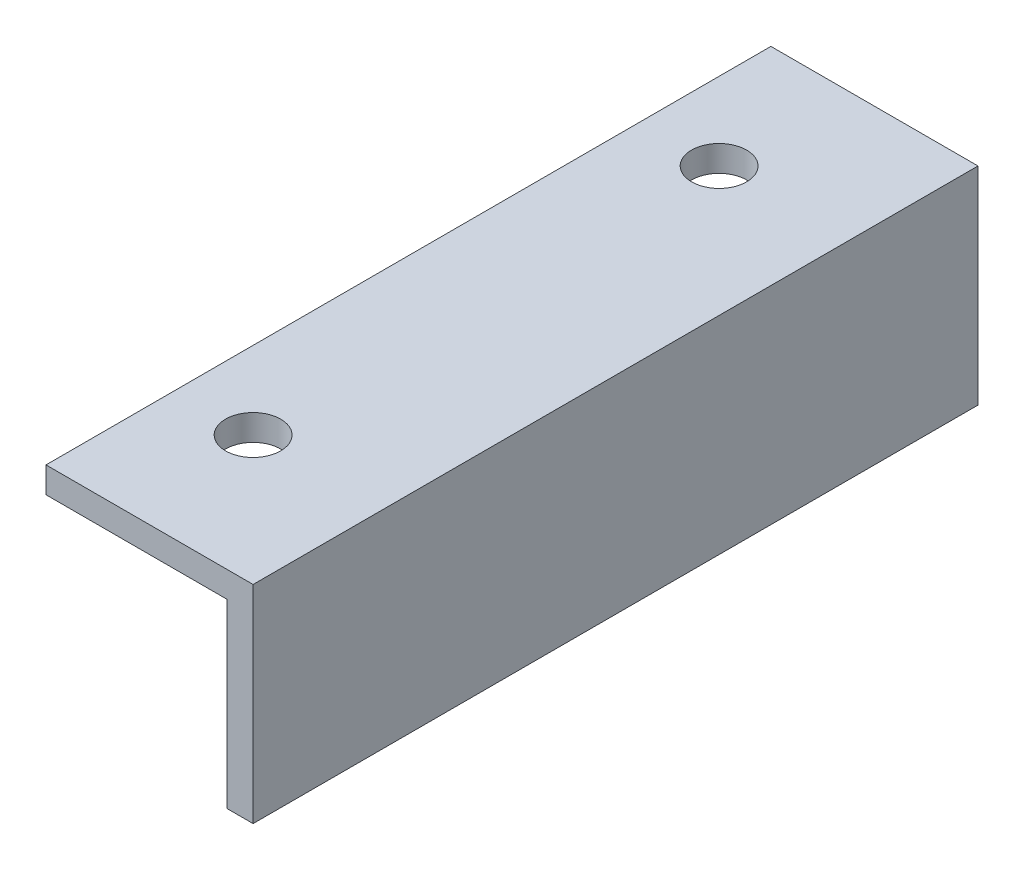
SolidWorks part; units mm, degrees
material "6061 Alloy"
ref_plane "Front" through (0, 0, 0) normal (0, 0, 1) x (1, 0, 0)
ref_plane "Top" through (0, 0, 0) normal (0, 1, 0) x (1, 0, 0)
ref_plane "Right" through (0, 0, 0) normal (1, 0, 0) x (0, 0, -1)
sketch "Sketch1" plane through (0, 0, 0) normal (0, 0, 1) x (1, 0, 0)
  line L0 (0, 0) -> (0, 25.4)
  line L1 (0, 25.4) -> (-25.4, 25.4)
  line L2 (-25.4, 25.4) -> (-25.4, 22.225)
  line L3 (-25.4, 22.225) -> (-3.175, 22.225)
  line L4 (-3.175, 22.225) -> (-3.175, 0)
  line L5 (-3.175, 0) -> (0, 0)
  dimension "D1" = 25.4
  dimension "D2" = 3.175
extrude "Boss-Extrude1" add sketch "Sketch1" along normal blind 88.9
sketch "Sketch2" plane through (0, 25.4, 0) normal (0, 1, 0) x (1, 0, 0)
  line L0 (0, -88.9) -> (0, 0) construction
  line L3 (-15.875, -15.875) -> (-15.875, 0) construction
  line L5 (-15.875, -88.9) -> (-15.875, -73.025) construction
  circle A0 centre (-15.875, -15.875) radius 3.3782
  circle A1 centre (-15.875, -73.025) radius 3.3782
  dimension "D1" = 15.875
  dimension "D2" = 6.7564
  dimension "D4" = 15.875
extrude "Cut-Extrude1" cut sketch "Sketch2" against normal through all
